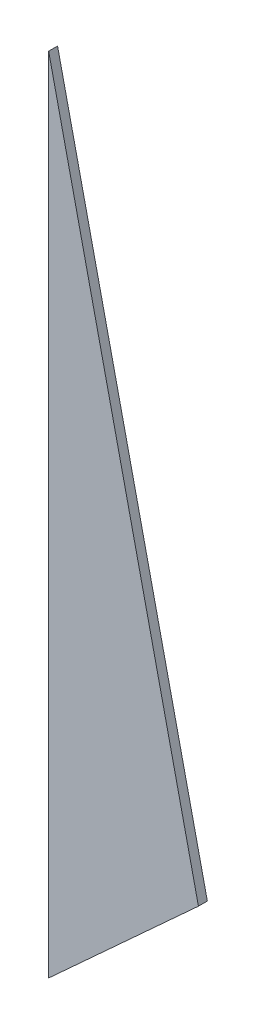
SolidWorks part; units mm, degrees
ref_plane "Front Plane" through (0, 0, 0) normal (0, 0, 1) x (1, 0, 0)
ref_plane "Top Plane" through (0, 0, 0) normal (0, 1, 0) x (1, 0, 0)
ref_plane "Right Plane" through (0, 0, 0) normal (1, 0, 0) x (0, 0, -1)
sketch "Sketch1" plane through (0, 0, 0) normal (0, 0, 1) x (1, 0, 0)
  line L0 (0, -45) -> (0, 45)
  line L1 (0, 45) -> (16.7943, -29.6323)
  line L2 (0, -45) -> (16.7943, -29.6323)
  line L4 (18, 252.3816) -> (18, -45) construction
  point P4 (0, 0)
extrude "Boss-Extrude1" add sketch "Sketch1" along normal mid plane 1
